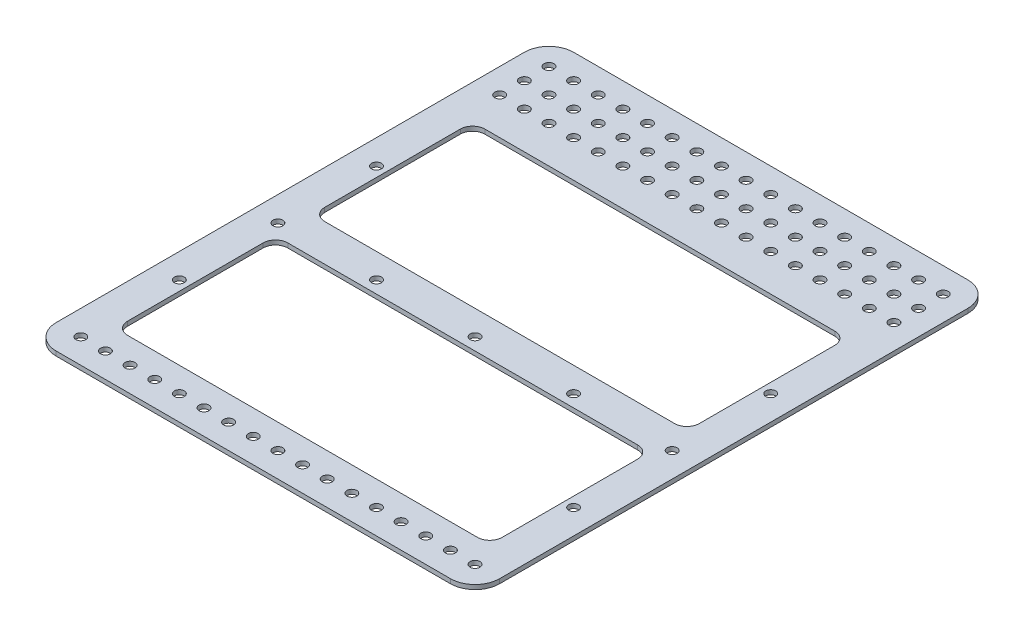
SolidWorks part; units mm, degrees
ref_plane "Front Plane" through (0, 0, 0) normal (0, 0, 1) x (1, 0, 0)
ref_plane "Top Plane" through (0, 0, 0) normal (0, 1, 0) x (1, 0, 0)
ref_plane "Right Plane" through (0, 0, 0) normal (1, 0, 0) x (0, 0, -1)
sketch "Sketch3" plane through (0, 0, 0) normal (0, 1, 0) x (1, 0, 0)
  point P0 (0, 0)
  line B0 (0, 0) -> (228.6, 0)
  line B1 (0, 0) -> (0, 266.7)
  line B2 (0, 266.7) -> (228.6, 266.7)
  line B3 (228.6, 0) -> (228.6, 266.7)
  line B4 (17.78, 107.95) -> (17.78, 25.4)
  line B5 (17.78, 107.95) -> (210.82, 107.95)
  line B6 (210.82, 107.95) -> (210.82, 25.4)
  line B7 (17.78, 127) -> (210.82, 127)
  line B8 (17.78, 127) -> (17.78, 209.55)
  line B9 (17.78, 209.55) -> (210.82, 209.55)
  line B10 (210.82, 127) -> (210.82, 209.55)
  circle B11 centre (12.7, 254) radius 2.54
  circle B12 centre (25.4, 254) radius 2.54
  circle B13 centre (38.1, 254) radius 2.54
  circle B14 centre (50.8, 254) radius 2.54
  circle B15 centre (63.5, 254) radius 2.54
  circle B16 centre (76.2, 254) radius 2.54
  circle B17 centre (88.9, 254) radius 2.54
  circle B18 centre (101.6, 254) radius 2.54
  circle B19 centre (114.3, 254) radius 2.54
  circle B20 centre (127, 254) radius 2.54
  circle B21 centre (139.7, 254) radius 2.54
  circle B22 centre (152.4, 254) radius 2.54
  circle B23 centre (165.1, 254) radius 2.54
  circle B24 centre (177.8, 254) radius 2.54
  circle B25 centre (190.5, 254) radius 2.54
  circle B26 centre (203.2, 254) radius 2.54
  circle B27 centre (215.9, 254) radius 2.54
  circle B28 centre (25.4, 241.3) radius 2.54
  circle B29 centre (38.1, 241.3) radius 2.54
  circle B30 centre (50.8, 241.3) radius 2.54
  circle B31 centre (63.5, 241.3) radius 2.54
  circle B32 centre (76.2, 241.3) radius 2.54
  circle B33 centre (88.9, 241.3) radius 2.54
  circle B34 centre (101.6, 241.3) radius 2.54
  circle B35 centre (114.3, 241.3) radius 2.54
  circle B36 centre (127, 241.3) radius 2.54
  circle B37 centre (139.7, 241.3) radius 2.54
  circle B38 centre (152.4, 241.3) radius 2.54
  circle B39 centre (165.1, 241.3) radius 2.54
  circle B40 centre (177.8, 241.3) radius 2.54
  circle B41 centre (190.5, 241.3) radius 2.54
  circle B42 centre (203.2, 241.3) radius 2.54
  circle B43 centre (215.9, 241.3) radius 2.54
  circle B44 centre (25.4, 228.6) radius 2.54
  circle B45 centre (38.1, 228.6) radius 2.54
  circle B46 centre (50.8, 228.6) radius 2.54
  circle B47 centre (63.5, 228.6) radius 2.54
  circle B48 centre (76.2, 228.6) radius 2.54
  circle B49 centre (88.9, 228.6) radius 2.54
  circle B50 centre (101.6, 228.6) radius 2.54
  circle B51 centre (114.3, 228.6) radius 2.54
  circle B52 centre (127, 228.6) radius 2.54
  circle B53 centre (139.7, 228.6) radius 2.54
  circle B54 centre (152.4, 228.6) radius 2.54
  circle B55 centre (165.1, 228.6) radius 2.54
  circle B56 centre (177.8, 228.6) radius 2.54
  circle B57 centre (190.5, 228.6) radius 2.54
  circle B58 centre (203.2, 228.6) radius 2.54
  circle B59 centre (215.9, 228.6) radius 2.54
  circle B60 centre (12.7, 241.3) radius 2.54
  circle B61 centre (12.7, 228.6) radius 2.54
  circle B62 centre (12.7, 12.7) radius 2.54
  circle B63 centre (25.4, 12.7) radius 2.54
  circle B64 centre (38.1, 12.7) radius 2.54
  circle B65 centre (50.8, 12.7) radius 2.54
  circle B66 centre (63.5, 12.7) radius 2.54
  circle B67 centre (76.2, 12.7) radius 2.54
  circle B68 centre (88.9, 12.7) radius 2.54
  circle B69 centre (101.6, 12.7) radius 2.54
  circle B70 centre (114.3, 12.7) radius 2.54
  circle B71 centre (127, 12.7) radius 2.54
  circle B72 centre (139.7, 12.7) radius 2.54
  circle B73 centre (152.4, 12.7) radius 2.54
  circle B74 centre (165.1, 12.7) radius 2.54
  circle B75 centre (177.8, 12.7) radius 2.54
  circle B76 centre (190.5, 12.7) radius 2.54
  circle B77 centre (203.2, 12.7) radius 2.54
  circle B78 centre (215.9, 12.7) radius 2.54
  circle B79 centre (12.7, 114.3) radius 2.54
  circle B80 centre (63.5, 114.3) radius 2.54
  circle B81 centre (114.3, 114.3) radius 2.54
  circle B82 centre (165.1, 114.3) radius 2.54
  circle B83 centre (215.9, 114.3) radius 2.54
  circle B84 centre (12.7, 165.1) radius 2.54
  circle B85 centre (215.9, 165.1) radius 2.54
  circle B86 centre (12.7, 63.5) radius 2.54
  circle B87 centre (215.9, 63.5) radius 2.54
  line B88 (17.78, 25.4) -> (210.82, 25.4)
sketch_block_instance "Block-Battery Holder-1"
sketch_block "Block-Battery Holder" parameters "D5"=5.08, "D10"=5.08, "D13"=5.08, "D1"=228.6, "D2"=19.05, "D3"=12.7, "D4"=12.7, "D6"=12.7, "D7"=12.7, "D8"=12.7, "D9"=12.7, "D11"=12.7, "D12"=12.7, "D14"=50.8, "D15"=50.8, "D16"=50.8, "D17"=76.2
extrude "Boss-Extrude3" add sketch "Sketch3" along normal blind 2.286
fillet "Fillet5" radius 12.7 4 edges at (0, 1.143, -266.7) (228.6, 1.143, -266.7) (228.6, 1.143, 0) (0, 1.143, 0)
fillet "Fillet6" radius 6.35 8 edges at (17.78, 1.143, -127) (210.82, 1.143, -127) (210.82, 1.143, -209.55) (17.78, 1.143, -209.55) (17.78, 1.143, -107.95) (17.78, 1.143, -25.4) (210.82, 1.143, -25.4) (210.82, 1.143, -107.95)
sketch "Sketch4" plane through (0, 0, 0) normal (0, -1, 0) x (1, 0, 0)
  line L0 (-1000, 0) -> (49000, 0) construction
  line L1 (0, -1000) -> (0, 49000) construction
  point P4 (0, 0)
  point P6 (0, 0)
sketch "Sketch5" [suppressed] plane through (0, 0, 0) normal (0, -1, 0) x (1, 0, 0)
  line L0 (204.47, -203.2) -> (24.13, -203.2) construction
  line L1 (17.78, -196.85) -> (17.78, -133.35) construction
  line L2 (55.88, -165.1) -> (170.18, -165.1) construction
  line L3 (55.88, -165.1) -> (55.88, -50.8) construction
  circle A0 centre (55.88, -165.1) radius 2.54
  circle A1 centre (170.18, -165.1) radius 2.54
  circle A2 centre (170.18, -50.8) radius 2.54
  circle A3 centre (55.88, -50.8) radius 2.54
  dimension "D1" = 38.1
  dimension "D2" = 38.1
  dimension "D3" = 5.08
  dimension "D6" = 114.3
  dimension "D7" = 114.3
  dimension "D4" = 2
  dimension "D5" = 2
